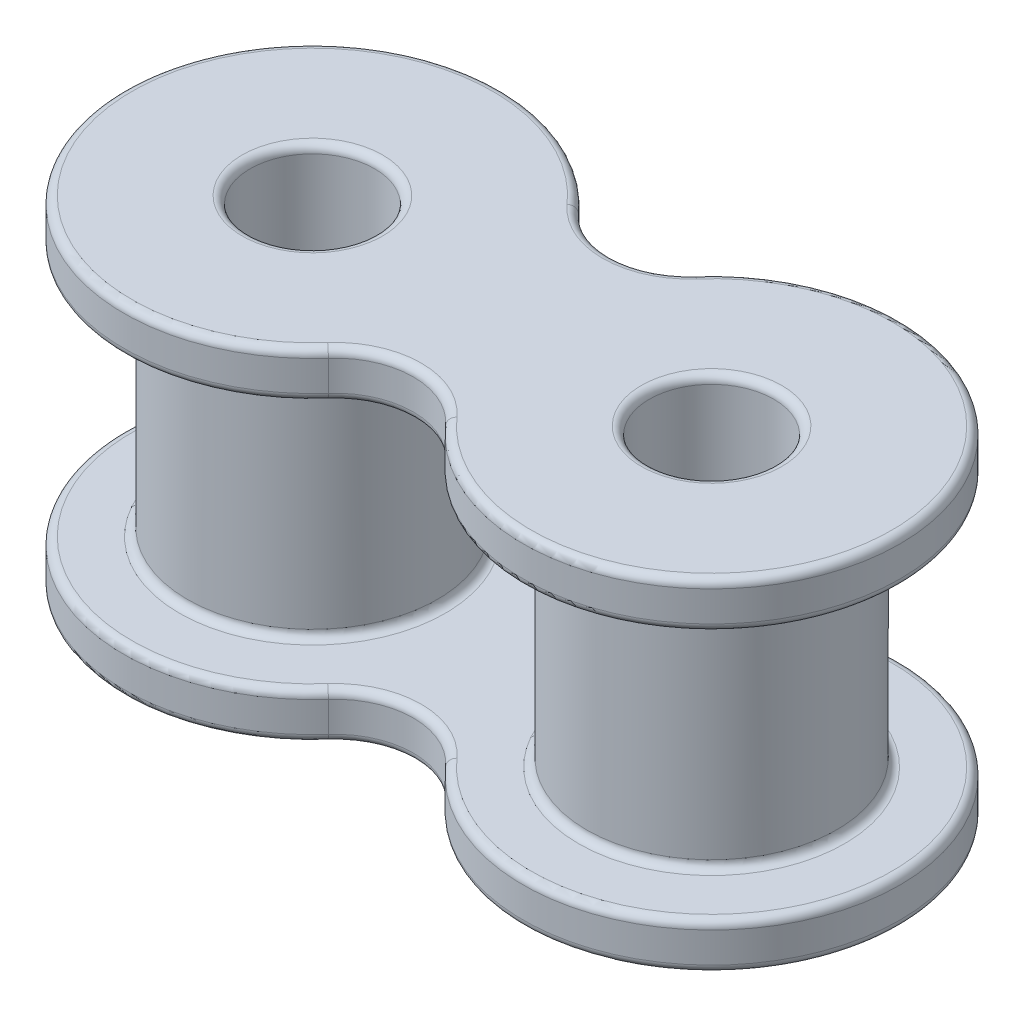
SolidWorks part; units mm, degrees
material "Alloy Steel"
ref_plane "X-Y Datum" through (0, 0, 0) normal (0, 0, 1) x (1, 0, 0)
ref_plane "X-Z Datum" through (0, 0, 0) normal (0, 1, 0) x (1, 0, 0)
ref_plane "Y-Z Datum" through (0, 0, 0) normal (1, 0, 0) x (0, 0, -1)
sketch "Sketch1" plane through (0, 0, 0) normal (0, 1, 0) x (1, 0, 0)
  line L0 (0, 9.8489) -> (0, -11.4215) construction
  line L1 (-12.6403, 0) -> (12.9549, 0) construction
  circle A0 centre (-6.35, 0) radius 1.9812
  arc A1 (-1.8654, 3.9776) -> (-1.8654, -3.9776) centre (-6.35, 0) ccw
  arc A2 (1.8654, 3.9776) -> (1.8654, -3.9776) centre (6.35, 0) cw
  circle A3 centre (6.35, 0) radius 1.9812
  arc A4 (-1.8654, 3.9776) -> (1.8654, 3.9776) centre (0, 5.6322) ccw
  arc A5 (-1.8654, -3.9776) -> (1.8654, -3.9776) centre (0, -5.6322) cw
  dimension "D1" = 11.9888
  dimension "D2" = 3.9624
  dimension "D4" = 2.4935
  dimension "D3" = 6.35
extrude "Boss-Extrude1" add sketch "Sketch1" along normal mid plane 1.4732
sketch "Sketch5" plane through (0, 0.7366, 0) normal (0, 1, 0) x (1, 0, 0)
  line L0 (0, -55) -> (0, 55) construction
  circle A0 centre (6.35, 0) radius 1.9812 construction
  circle A1 centre (6.35, 0) radius 1.9812
  circle A2 centre (-6.35, 0) radius 1.9812
  circle A3 centre (6.35, 0) radius 3.9751
  circle A4 centre (-6.35, 0) radius 3.9751
  dimension "D1" = 7.9502
extrude "Boss-Extrude2" add sketch "Sketch5" along normal blind 7.9248
fillet "Fillet" radius 0.254 12 edges at (0, 0.7366, -3.1387) (12.3444, 0.7366, 0) (0, 0.7366, 3.1387) (-12.3444, -0.7366, 0) (0, -0.7366, -3.1387) (-12.3444, 0.7366, 0) (6.35, -0.7366, -1.9812) (-6.35, -0.7366, 1.9812) (0, -0.7366, 3.1387) (12.3444, -0.7366, 0) (6.35, 0.7366, 3.9751) (-6.35, 0.7366, -3.9751)
ref_plane "Center Plane" through (0, 4.699, 0) normal (0, 1, 0) x (1, 0, 0)
mirror "Mirror2" about plane through (0, 4.699, 0) normal (0, 1, 0) of "Fillet", "Boss-Extrude1"
